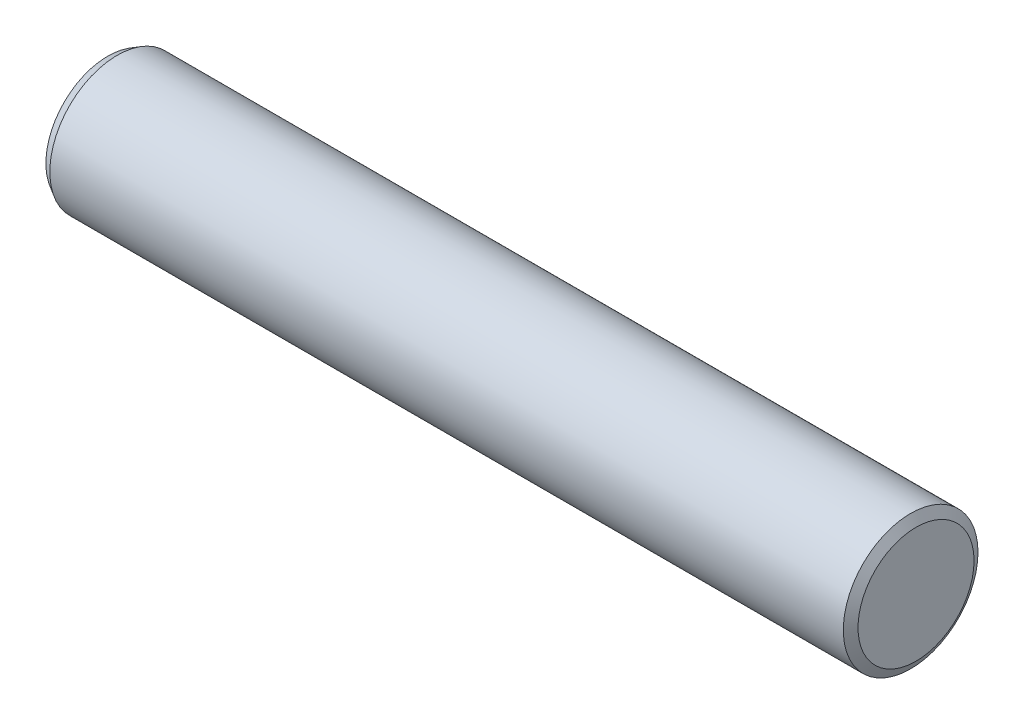
SolidWorks part; units mm, degrees
ref_plane "Front Plane" through (0, 0, 0) normal (0, 0, 1) x (1, 0, 0)
ref_plane "Top Plane" through (0, 0, 0) normal (0, 1, 0) x (1, 0, 0)
ref_plane "Right Plane" through (0, 0, 0) normal (1, 0, 0) x (0, 0, -1)
sketch "Sketch1" plane through (0, 0, 0) normal (0, 0, 1) x (1, 0, 0)
  line L1 (0, 0) -> (-30, 0)
  line L2 (0, 0) -> (0, 2.5)
  line L3 (0, 2.5) -> (-30, 2.5)
  line L4 (-30, 0) -> (-30, 2.5)
  dimension "D1" = 30
  dimension "D2" = 2.5
revolve "Revolve1" add sketch "Sketch1" angle 360 about L1
chamfer "Chamfer1" distance 0.2 angle 60 2 edges at (0, 0, -2.5) (-30, 0, -2.5)
ref_plane "Plane1" through (-15, 0, 0) normal (1, 0, 0) x (0, 0, -1)
